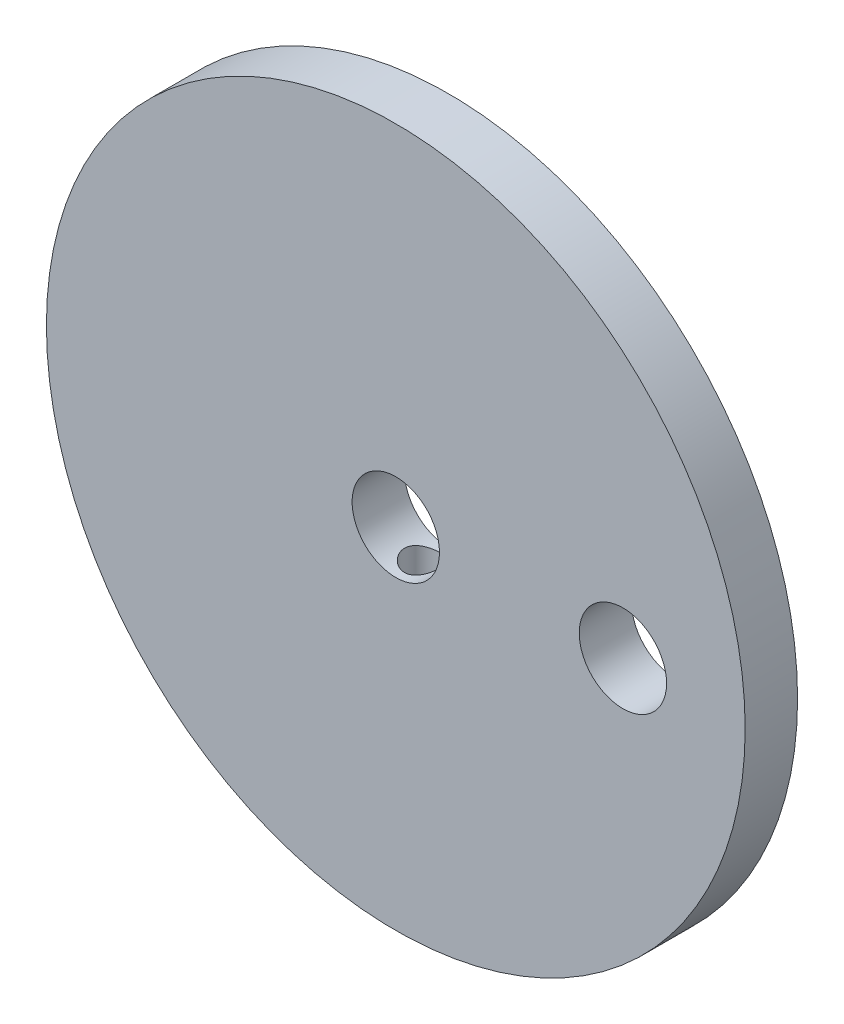
SolidWorks part; units mm, degrees
ref_plane "前视基准面" through (0, 0, 0) normal (0, 0, 1) x (1, 0, 0)
ref_plane "上视基准面" through (0, 0, 0) normal (0, 1, 0) x (1, 0, 0)
ref_plane "右视基准面" through (0, 0, 0) normal (1, 0, 0) x (0, 0, -1)
sketch "草图1" plane through (0, 0, 0) normal (0, 0, 1) x (1, 0, 0)
  circle A0 centre (0, 0) radius 20
  dimension "D1" = 40
extrude "凸台-拉伸1" add sketch "草图1" along normal blind 3
sketch "草图2" plane through (0, 0, 3) normal (0, 0, 1) x (1, 0, 0)
  circle A0 centre (0, 0) radius 2.5
  dimension "D1" = 5
extrude "切除-拉伸1" cut sketch "草图2" against normal through all
sketch "草图4" plane through (0, 0, 3) normal (0, 0, 1) x (1, 0, 0)
  circle A0 centre (0, 0) radius 13 construction
  circle A1 centre (13, 0) radius 2.5
  dimension "D1" = 26
  dimension "D2" = 5
extrude "切除-拉伸2" cut sketch "草图4" against normal through all
hole_wizard "Ø2.0mm 暗销孔1" positions "3D草图1" profile "草图5" hole size "Ø2.0" standard "GB"
sketch3d "3D草图1"
  point P0 (0, -20, 1.5)
  point P3 (0, 0, 0)
  dimension "D1" = 1.5
sketch "草图5" plane through (0, -20, 1.5) normal (1, 0, 0) x (0, 0, -1)
  line L0 (0, 0) -> (0, 17.5)
  line L1 (0, 17.5) -> (1, 17.5)
  line L2 (1, 17.5) -> (1, 0)
  line L5 (1, 0) -> (0, 0)
  line L11 (0, -6.35) -> (0, 107.95) construction
  dimension "通孔孔直径" = 2
  dimension "通孔孔深度" = 17.5
